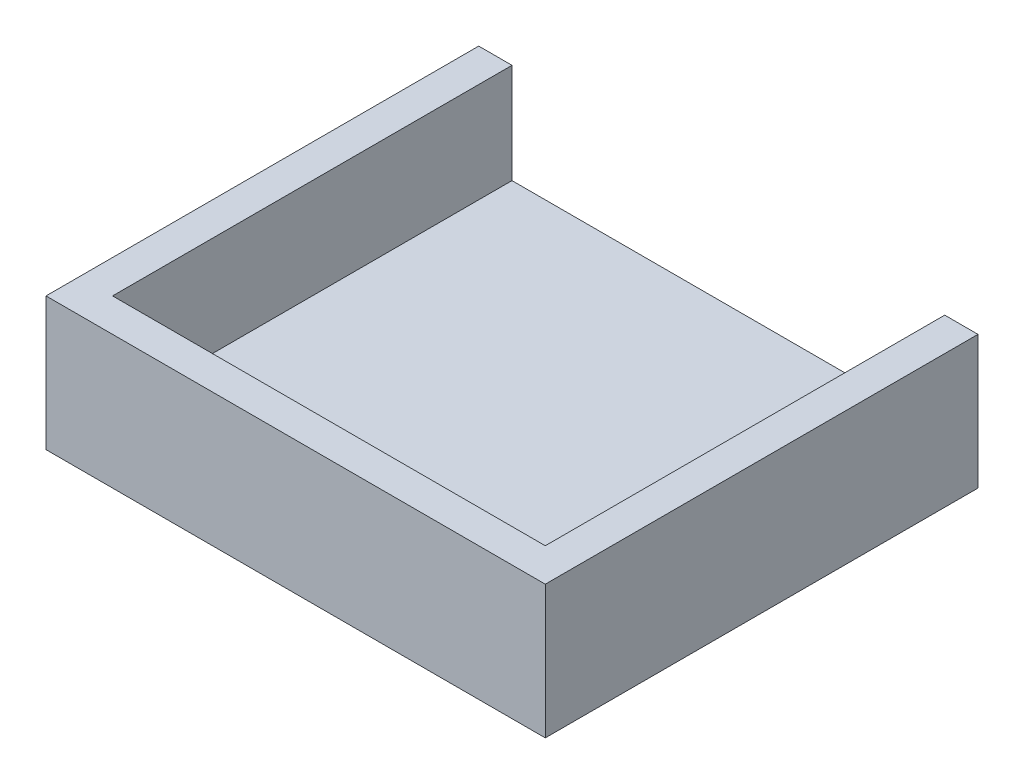
SolidWorks part; units mm, degrees
ref_plane "정면" through (0, 0, 0) normal (0, 0, 1) x (1, 0, 0)
ref_plane "윗면" through (0, 0, 0) normal (0, 1, 0) x (1, 0, 0)
ref_plane "우측면" through (0, 0, 0) normal (1, 0, 0) x (0, 0, -1)
sketch "스케치1" plane through (0, 0, 0) normal (0, 1, 0) x (1, 0, 0)
  line L1 (7.5, -6.5) -> (-7.5, -6.5)
  line L2 (7.5, -6.5) -> (7.5, 6.5)
  line L3 (7.5, 6.5) -> (-7.5, 6.5)
  line L4 (-7.5, -6.5) -> (-7.5, 6.5)
  line L5 (7.5, -6.5) -> (-7.5, 6.5) construction
  line L6 (7.5, 6.5) -> (-7.5, -6.5) construction
  point P0 (0, 0)
  dimension "D1" = 15
  dimension "D2" = 13
extrude "보스-돌출1" add sketch "스케치1" along normal blind 4
sketch "스케치2" plane through (0, 0, 0) normal (0, 1, 0) x (1, 0, 0)
  line L0 (-7.5, -6.5) -> (7.5, -6.5) construction
  line L1 (-6.5, 9.5) -> (6.5, 9.5)
  line L2 (-6.5, 9.5) -> (-6.5, -5.5)
  line L3 (-6.5, -5.5) -> (6.5, -5.5)
  line L4 (6.5, 9.5) -> (6.5, -5.5)
  line L5 (7.5, -6.5) -> (7.5, 6.5) construction
  dimension "D1" = 13
  dimension "D2" = 15
  dimension "D3" = 1
  dimension "D4" = 1
extrude "컷-돌출1" cut sketch "스케치2" along normal blind 4 from offset 1
sketch "스케치3" plane through (0, 0, 0) normal (0, 1, 0) x (1, 0, 0)
  line L1 (7.5, -6.5) -> (-7.5, -6.5)
  line L2 (7.5, -6.5) -> (7.5, 6.5)
  line L3 (7.5, 6.5) -> (-7.5, 6.5)
  line L4 (-7.5, -6.5) -> (-7.5, 6.5)
  line L5 (7.5, -6.5) -> (-7.5, 6.5) construction
  line L6 (7.5, 6.5) -> (-7.5, -6.5) construction
  point P0 (0, 0)
extrude "보스-돌출3" add sketch "스케치3" along normal blind 1 from offset 4 separate body
sketch "스케치4" plane through (0, 0, 0) normal (0, 1, 0) x (1, 0, 0)
  line L0 (-7.5, -6.5) -> (7.5, -6.5) construction
  line L1 (-0.5, 1.5) -> (5.5, 1.5)
  line L2 (-0.5, 1.5) -> (-0.5, -4.5)
  line L3 (-0.5, -4.5) -> (5.5, -4.5)
  line L4 (5.5, 1.5) -> (5.5, -4.5)
  line L5 (7.5, -6.5) -> (7.5, 6.5) construction
  dimension "D1" = 6
  dimension "D2" = 6
  dimension "D3" = 2
  dimension "D4" = 2
extrude "컷-돌출2" cut sketch "스케치4" against normal blind 1 from surface at 5 starting at face at (0, 5, 0)
sketch "스케치5" plane through (0, 5, 0) normal (0, 1, 0) x (1, 0, 0)
  line L4 (-7.5, 6.5) -> (-7.5, -6.5)
  line L5 (-7.5, -6.5) -> (7.5, -6.5)
  line L6 (7.5, -6.5) -> (7.5, 6.5)
  line L7 (7.5, 6.5) -> (-7.5, 6.5)
  line L8 (-7.5, 6.5) -> (-7.5, -6.5)
  line L9 (-7.5, -6.5) -> (7.5, -6.5)
  line L10 (7.5, -6.5) -> (7.5, 6.5)
  line L11 (7.5, 6.5) -> (-7.5, 6.5)
  dimension "D1" = 0
extrude "컷-돌출3" cut sketch "스케치5" against normal blind 1
